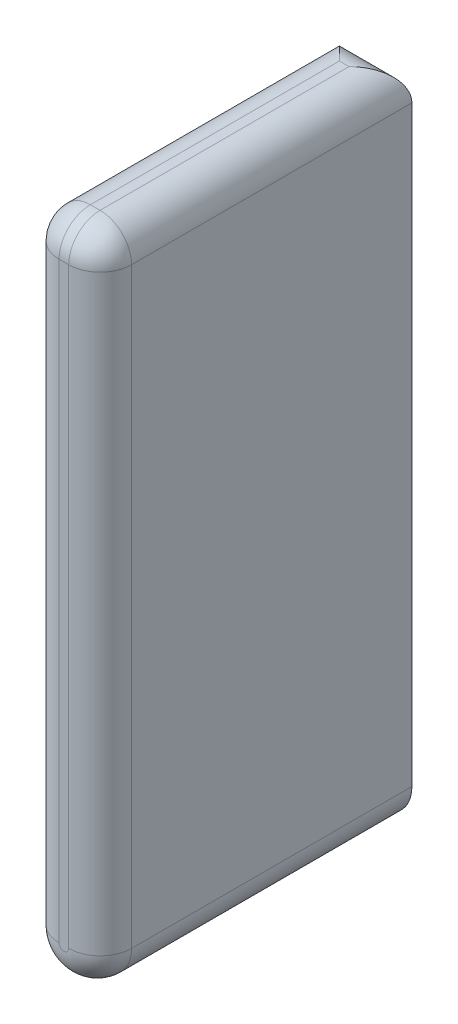
SolidWorks part; units mm, degrees
ref_plane "Front Plane" through (0, 0, 0) normal (0, 0, 1) x (1, 0, 0)
ref_plane "Top Plane" through (0, 0, 0) normal (0, 1, 0) x (1, 0, 0)
ref_plane "Right Plane" through (0, 0, 0) normal (1, 0, 0) x (0, 0, -1)
sketch "Sketch1" plane through (0, 0, 0) normal (0, 0, 1) x (1, 0, 0)
  circle A0 centre (0, 0) radius 75
  dimension "D1" = 150
extrude "Boss-Extrude1" add sketch "Sketch1" along normal blind 645
sketch "Sketch2" plane through (0, 0, 0) normal (0, 1, 0) x (1, 0, 0)
  line L1 (-75, 0) -> (75, 0)
  line L2 (-75, 0) -> (-75, -645)
  line L3 (-75, -645) -> (75, -645)
  line L4 (75, 0) -> (75, -645)
extrude "Boss-Extrude2" add sketch "Sketch2" along normal blind 1290
fillet "Fillet1" radius 65 7 edges at (75, 645, 645) (0, -75, 645) (0, 1290, 0) (75, 1290, 322.5) (0, 1290, 645) (-75, 1290, 322.5) (-75, 645, 645)
